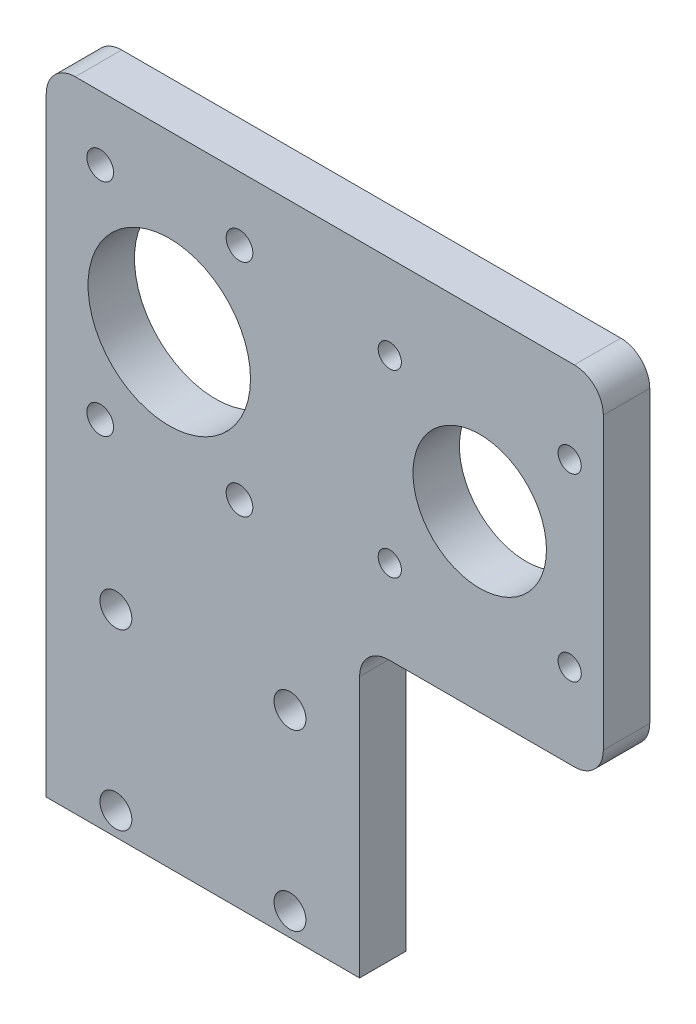
SolidWorks part; units mm, degrees
ref_plane "前视基准面" through (0, 0, 0) normal (0, 0, 1) x (1, 0, 0)
ref_plane "上视基准面" through (0, 0, 0) normal (0, 1, 0) x (1, 0, 0)
ref_plane "右视基准面" through (0, 0, 0) normal (1, 0, 0) x (0, 0, -1)
other "Configuration Table"
sketch "草图1" plane through (0, 0, 0) normal (0, 0, 1) x (1, 0, 0)
  line L0 (27, -110) -> (27, -10) construction
  line L1 (0, 0) -> (54, 0)
  line L2 (0, 0) -> (0, -110)
  line L3 (0, -110) -> (54, -110)
  line L4 (54, -60) -> (54, -110)
  line L5 (54, 0) -> (96, 0)
  line L7 (54, -60) -> (96, -60)
  line L8 (96, 0) -> (96, -60)
  line L9 (75, -60) -> (75, -18) construction
  circle A0 centre (12, -106) radius 2.75
  circle A1 centre (42, -106) radius 2.75
  circle A2 centre (42, -76) radius 2.75
  circle A3 centre (12, -76) radius 2.75
  circle A4 centre (21.2, -30) radius 14
  circle A5 centre (74.7, -30) radius 11.5
  circle A6 centre (59.2, -14.5) radius 2
  circle A7 centre (90.2, -14.5) radius 2
  circle A8 centre (90.2, -45.5) radius 2
  circle A9 centre (59.2, -45.5) radius 2
  point P25 (0, 0)
  point P28 (0, 0)
  dimension "D7" = 5.5
  dimension "D11" = 28
  dimension "D13" = 23
  dimension "D12" = 4
  dimension "D1" = 54
  dimension "D2" = 110
  dimension "D3" = 42
  dimension "D4" = 60
  dimension "D5" = 54
  dimension "D6" = 4
  dimension "D8" = 15
  dimension "D14" = 15.5
  dimension "D15" = 15.5
  dimension "D18" = 30
  dimension "D19" = 21.2
  dimension "D20" = 53.5
  dimension "D9" = 2
  dimension "D10" = 2
  dimension "D16" = 2
  dimension "D17" = 2
extrude "凸台-拉伸1" add sketch "草图1" along normal blind 8
fillet "圆角1" radius 5 4 edges at (54, -60, 4) (96, -60, 4) (96, 0, 4) (0, 0, 4)
sketch "草图2" plane through (0, 0, 8) normal (0, 0, 1) x (1, 0, 0)
  line L0 (0, -5) -> (0, -110) construction
  line L1 (91, 0) -> (5, 0) construction
  circle A0 centre (9.3, -11) radius 2.3
  circle A1 centre (33.3, -11) radius 2.3
  circle A2 centre (33.3, -49) radius 2.3
  circle A3 centre (9.3, -49) radius 2.3
  dimension "D1" = 4.6
  dimension "D2" = 9.3
  dimension "D3" = 11
  dimension "D4" = 2
  dimension "D5" = 2
extrude "切除-拉伸1" cut sketch "草图2" against normal blind 10
sketch "草图3" plane through (0, 0, 8) normal (0, 0, 1) x (1, 0, 0)
  line L0 (21.2, -18.925) -> (74.9997, -18.9291) construction
  line L1 (21.2, -41.075) -> (74.9997, -41.0709) construction
  arc A0 (74.9997, -41.0709) -> (74.9997, -18.9291) centre (74.7, -30) ccw construction
  arc A1 (21.2, -18.925) -> (21.2, -41.075) centre (21.2, -30) ccw construction
  dimension "D1" = 22.15
  dimension "D2" = 22.15
